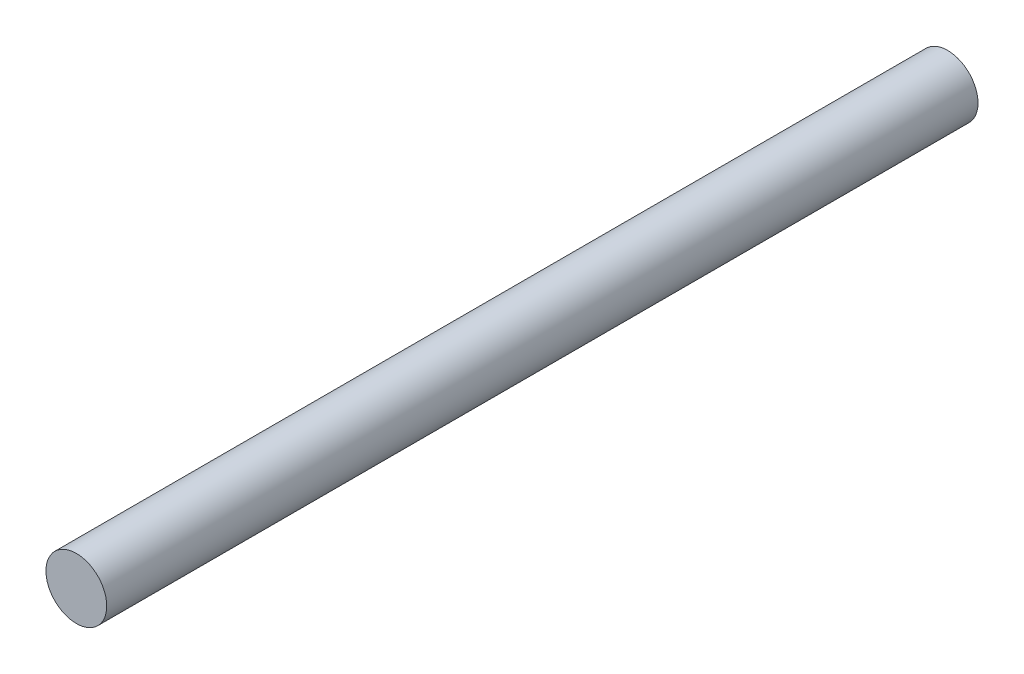
SolidWorks part; units mm, degrees
ref_plane "Front Plane" through (0, 0, 0) normal (0, 0, 1) x (1, 0, 0)
ref_plane "Top Plane" through (0, 0, 0) normal (0, 1, 0) x (1, 0, 0)
ref_plane "Right Plane" through (0, 0, 0) normal (1, 0, 0) x (0, 0, -1)
sketch "Sketch1" plane through (0, 0, 0) normal (0, 0, 1) x (1, 0, 0)
  circle A0 centre (0, 0) radius 1.5
  dimension "D1" = 3
extrude "Boss-Extrude1" add sketch "Sketch1" along normal blind 43
